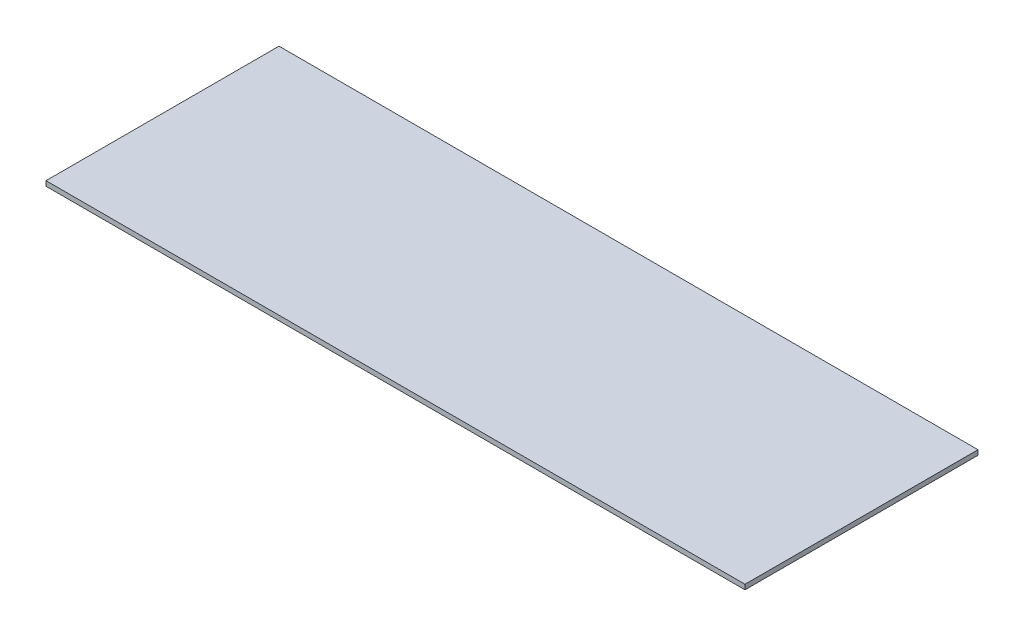
SolidWorks part; units mm, degrees
material "ABS PC"
ref_plane "Front Plane" through (0, 0, 0) normal (0, 0, 1) x (1, 0, 0)
ref_plane "Top Plane" through (0, 0, 0) normal (0, 1, 0) x (1, 0, 0)
ref_plane "Right Plane" through (0, 0, 0) normal (1, 0, 0) x (0, 0, -1)
sketch "Sketch1" plane through (0, 0, 0) normal (0, 1, 0) x (1, 0, 0)
  line L1 (0, 0) -> (457.2, 0)
  line L2 (0, 0) -> (0, 152.4)
  line L3 (0, 152.4) -> (457.2, 152.4)
  line L4 (457.2, 0) -> (457.2, 152.4)
  dimension "D1" = 457.2
  dimension "D2" = 152.4
extrude "Boss-Extrude1" add sketch "Sketch1" along normal blind 3.175
